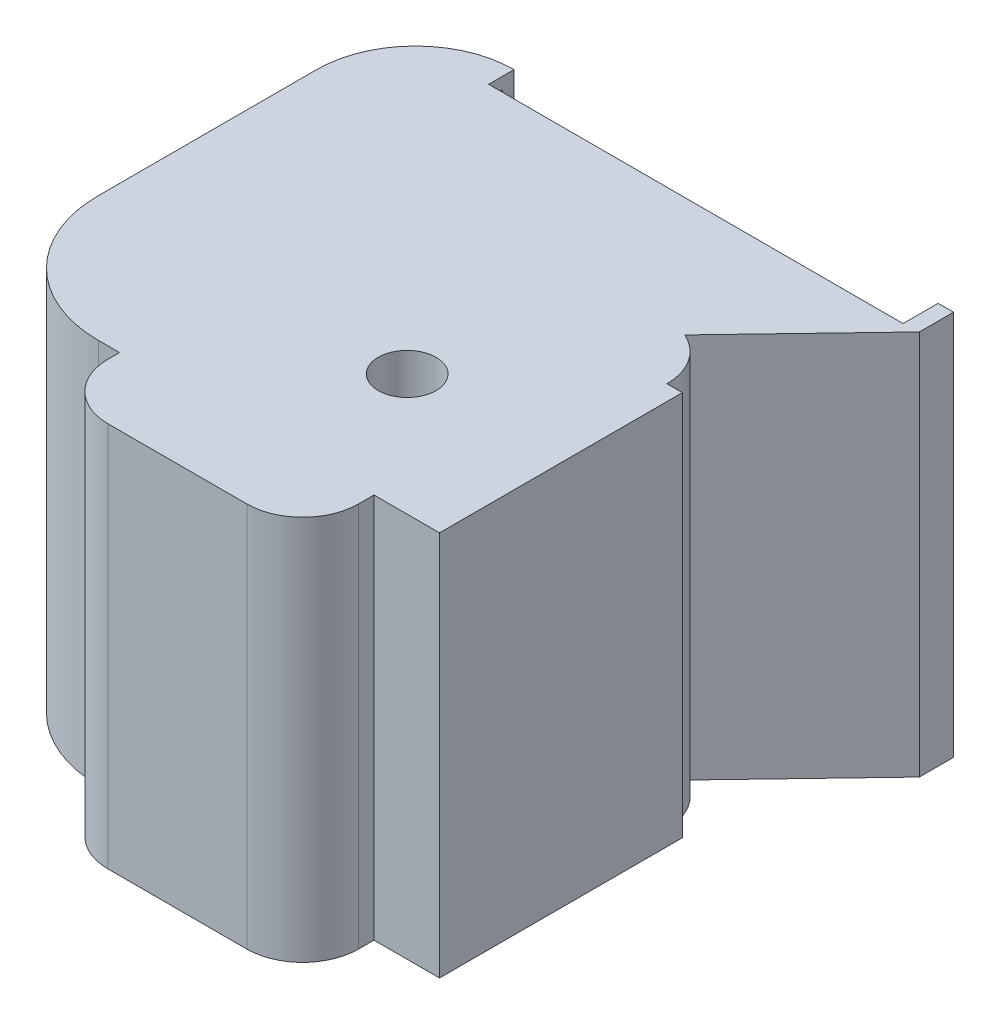
SolidWorks part; units mm, degrees
ref_plane "Front Plane" through (0, 0, 0) normal (0, 0, 1) x (1, 0, 0)
ref_plane "Top Plane" through (0, 0, 0) normal (0, 1, 0) x (1, 0, 0)
ref_plane "Right Plane" through (0, 0, 0) normal (1, 0, 0) x (0, 0, -1)
sketch "Sketch1" plane through (0, 0, 0) normal (0, 1, 0) x (1, 0, 0)
  line L0 (6.7619, 6.3187) -> (3.0619, 2.8572) construction
  line L1 (3.0619, 2.8572) -> (3.1519, 2.6951) construction
  line L2 (3.1519, 2.6951) -> (3.6519, 2.6951) construction
  line L3 (4.6519, 1.2451) -> (4.6519, 1.6951) construction
  line L4 (4.6519, 1.2451) -> (5.0519, 1.2451) construction
  line L5 (5.0519, 1.2451) -> (5.0519, -4.1549) construction
  line L6 (5.0519, -4.1549) -> (3.3519, -4.1549) construction
  line L7 (3.3519, -4.1549) -> (3.3519, -5.0049) construction
  line L8 (2.3519, -6.0049) -> (-1.2481, -6.0049) construction
  line L9 (-2.2481, -5.0049) -> (-2.2481, -4.2549) construction
  line L10 (-2.2481, -4.2549) -> (-3.2481, -4.2549) construction
  line L11 (-6.0481, -1.4549) -> (-6.0481, 4.2087) construction
  line L12 (6.7619, 6.3187) -> (6.7619, 7.0187) construction
  line L13 (6.9119, 6.2536) -> (6.9119, 7.0187)
  line L14 (3.6519, 2.8451) -> (6.9119, 6.2536)
  line L15 (-6.4981, -1.4549) -> (-6.4981, 4.2087)
  line L16 (-2.6981, -4.7049) -> (-3.2481, -4.7049)
  line L17 (4.8019, 1.3951) -> (4.8019, 1.6951)
  line L18 (4.8019, 1.3951) -> (5.2019, 1.3951)
  line L19 (5.2019, 1.3951) -> (5.2019, -4.3049)
  line L20 (5.2019, -4.3049) -> (3.5019, -4.3049)
  line L21 (3.5019, -4.3049) -> (3.5019, -5.0049)
  line L22 (2.3519, -6.1549) -> (-1.2481, -6.1549)
  line L23 (-2.3981, -5.0049) -> (-2.3981, -4.4049)
  line L24 (-2.3981, -4.4049) -> (-3.2481, -4.4049)
  line L25 (-6.1981, -1.4549) -> (-6.1981, 4.2087)
  line L26 (6.9119, 6.2536) -> (3.2686, 2.8451) construction
  line L27 (3.2686, 2.8451) -> (3.6519, 2.8451) construction
  line L28 (3.2686, 2.8451) -> (3.2686, 2.8451) construction
  line L29 (-2.6981, -5.0049) -> (-2.6981, -4.7049)
  line L30 (2.3519, -6.4549) -> (-1.2481, -6.4549)
  line L31 (3.8019, -4.6049) -> (3.8019, -5.0049)
  line L32 (5.5019, -4.6049) -> (3.8019, -4.6049)
  line L33 (5.5019, 1.6951) -> (5.5019, -4.6049)
  line L34 (5.1019, 1.6951) -> (5.5019, 1.6951)
  line L35 (5.1019, 1.6951) -> (5.1019, 1.6951)
  line L36 (4.2363, 3.0221) -> (7.2119, 6.1332)
  line L37 (7.2119, 6.1332) -> (7.2119, 7.0187)
  line L38 (-3.9381, 6.7687) -> (-3.9381, 6.4687)
  line L39 (6.9119, 7.0187) -> (7.2119, 7.0187)
  arc A0 (3.6519, 2.6951) -> (4.6519, 1.6951) centre (3.6519, 1.6951) cw construction
  arc A1 (-2.2481, -5.0049) -> (-1.2481, -6.0049) centre (-1.2481, -5.0049) ccw construction
  arc A2 (2.3519, -6.0049) -> (3.3519, -5.0049) centre (2.3519, -5.0049) ccw construction
  arc A3 (-6.0481, 4.2087) -> (-3.9381, 6.3187) centre (-3.9381, 4.2087) cw construction
  arc A4 (-6.0481, -1.4549) -> (-3.2481, -4.2549) centre (-3.2481, -1.4549) ccw construction
  arc A5 (3.6519, 2.8451) -> (4.8019, 1.6951) centre (3.6519, 1.6951) cw
  arc A6 (2.3519, -6.1549) -> (3.5019, -5.0049) centre (2.3519, -5.0049) ccw
  arc A7 (-2.3981, -5.0049) -> (-1.2481, -6.1549) centre (-1.2481, -5.0049) ccw
  arc A8 (-6.1981, -1.4549) -> (-3.2481, -4.4049) centre (-3.2481, -1.4549) ccw
  arc A9 (-6.1981, 4.2087) -> (-3.9381, 6.4687) centre (-3.9381, 4.2087) cw
  arc A10 (-6.4981, 4.2087) -> (-3.9381, 6.7687) centre (-3.9381, 4.2087) cw
  arc A11 (-6.4981, -1.4549) -> (-3.2481, -4.7049) centre (-3.2481, -1.4549) ccw
  arc A12 (-2.6981, -5.0049) -> (-1.2481, -6.4549) centre (-1.2481, -5.0049) ccw
  arc A13 (2.3519, -6.4549) -> (3.8019, -5.0049) centre (2.3519, -5.0049) ccw
  arc A14 (4.2363, 3.0221) -> (5.1019, 1.6951) centre (3.6519, 1.6951) cw
  dimension "D1" = 0.7
  dimension "D2" = 0.15
  dimension "D3" = 0.3
extrude "Boss-Extrude2" add sketch "Sketch1" along normal blind 8.2 and the other way blind 1.5
sketch "Sketch6" plane through (0, 8.2, 0) normal (0, 1, 0) x (1, 0, 0)
  line L0 (-3.9381, 6.7687) -> (6.9119, 7.0187)
  line L23 (6.9119, 6.2536) -> (3.6519, 2.8451)
  line L24 (4.8019, 1.6951) -> (4.8019, 1.3951)
  line L25 (4.8019, 1.3951) -> (5.2019, 1.3951)
  line L26 (5.2019, 1.3951) -> (5.2019, -4.3049)
  line L27 (5.2019, -4.3049) -> (3.5019, -4.3049)
  line L28 (3.5019, -4.3049) -> (3.5019, -5.0049)
  line L29 (2.3519, -6.1549) -> (-1.2481, -6.1549)
  line L30 (-2.3981, -5.0049) -> (-2.3981, -4.4049)
  line L31 (-2.3981, -4.4049) -> (-3.2481, -4.4049)
  line L32 (-6.1981, -1.4549) -> (-6.1981, 4.2087)
  line L33 (-3.9381, 6.4687) -> (-3.9381, 6.7687)
  line L34 (-6.4981, 4.2087) -> (-6.4981, -1.4549)
  line L35 (-3.2481, -4.7049) -> (-2.6981, -4.7049)
  line L36 (-2.6981, -4.7049) -> (-2.6981, -5.0049)
  line L37 (-1.2481, -6.4549) -> (2.3519, -6.4549)
  line L38 (3.8019, -5.0049) -> (3.8019, -4.6049)
  line L39 (3.8019, -4.6049) -> (5.5019, -4.6049)
  line L40 (5.5019, -4.6049) -> (5.5019, 1.6951)
  line L41 (5.5019, 1.6951) -> (5.1019, 1.6951)
  line L42 (4.2363, 3.0221) -> (7.2119, 6.1332)
  line L43 (7.2119, 6.1332) -> (7.2119, 7.0187)
  line L44 (7.2119, 7.0187) -> (6.9119, 7.0187)
  line L45 (6.9119, 7.0187) -> (6.9119, 6.2536)
  line L57 (-6.4981, 4.2087) -> (-6.4981, -1.4549)
  line L58 (-3.2481, -4.7049) -> (-2.6981, -4.7049)
  line L59 (-2.6981, -4.7049) -> (-2.6981, -5.0049)
  line L60 (-1.2481, -6.4549) -> (2.3519, -6.4549)
  line L61 (3.8019, -5.0049) -> (3.8019, -4.6049)
  line L62 (3.8019, -4.6049) -> (5.5019, -4.6049)
  line L63 (5.5019, -4.6049) -> (5.5019, 1.6951)
  line L64 (5.5019, 1.6951) -> (5.1019, 1.6951)
  line L65 (4.2363, 3.0221) -> (7.2119, 6.1332)
  line L66 (7.2119, 6.1332) -> (7.2119, 7.0187)
  line L67 (7.2119, 7.0187) -> (6.9119, 7.0187)
  arc A10 (4.8019, 1.6951) -> (3.6519, 2.8451) centre (3.6519, 1.6951) ccw
  arc A11 (2.3519, -6.1549) -> (3.5019, -5.0049) centre (2.3519, -5.0049) ccw
  arc A12 (-2.3981, -5.0049) -> (-1.2481, -6.1549) centre (-1.2481, -5.0049) ccw
  arc A13 (-6.1981, -1.4549) -> (-3.2481, -4.4049) centre (-3.2481, -1.4549) ccw
  arc A14 (-3.9381, 6.4687) -> (-6.1981, 4.2087) centre (-3.9381, 4.2087) ccw
  arc A15 (-3.9381, 6.7687) -> (-6.4981, 4.2087) centre (-3.9381, 4.2087) ccw
  arc A16 (-6.4981, -1.4549) -> (-3.2481, -4.7049) centre (-3.2481, -1.4549) ccw
  arc A17 (-2.6981, -5.0049) -> (-1.2481, -6.4549) centre (-1.2481, -5.0049) ccw
  arc A18 (2.3519, -6.4549) -> (3.8019, -5.0049) centre (2.3519, -5.0049) ccw
  arc A19 (5.1019, 1.6951) -> (4.2363, 3.0221) centre (3.6519, 1.6951) ccw
  arc A25 (-3.9381, 6.7687) -> (-6.4981, 4.2087) centre (-3.9381, 4.2087) ccw
  arc A26 (-6.4981, -1.4549) -> (-3.2481, -4.7049) centre (-3.2481, -1.4549) ccw
  arc A27 (-2.6981, -5.0049) -> (-1.2481, -6.4549) centre (-1.2481, -5.0049) ccw
  arc A28 (2.3519, -6.4549) -> (3.8019, -5.0049) centre (2.3519, -5.0049) ccw
  arc A29 (5.1019, 1.6951) -> (4.2363, 3.0221) centre (3.6519, 1.6951) ccw
  dimension "D1" = 0
extrude "Boss-Extrude3" add sketch "Sketch6" along normal blind 0.3
sketch "Sketch7" plane through (0, 8.5, 0) normal (0, 1, 0) x (1, 0, 0)
  line L0 (-3.9381, 6.7687) -> (-3.9381, 6.1087)
  line L1 (-3.9381, 6.1087) -> (6.8119, 6.1087)
  line L2 (6.8119, 6.1087) -> (6.8119, 7.0164)
  line L3 (6.9119, 7.0187) -> (-3.9381, 6.7687) construction
  line L5 (-3.9381, 6.7687) -> (6.8119, 7.0164)
  circle A0 centre (1.5119, -1.4549) radius 0.75
  circle A1 centre (1.5119, -1.4549) radius 1.1 construction
  dimension "D3" = 1.5
  dimension "D1" = 10.75
  dimension "D2" = 0.66
extrude "Cut-Extrude2" cut sketch "Sketch7" against normal blind 0.3
sketch "Sketch8" plane through (0, 8.2, 0) normal (0, -1, 0) x (1, 0, 0)
  circle A0 centre (1.5119, 1.4549) radius 1.1
  circle A1 centre (1.5119, 1.4549) radius 0.75
  circle A2 centre (1.5119, 1.4549) radius 0.75 construction
  dimension "D1" = 0.35
extrude "Boss-Extrude4" add sketch "Sketch8" along normal blind 4.45
